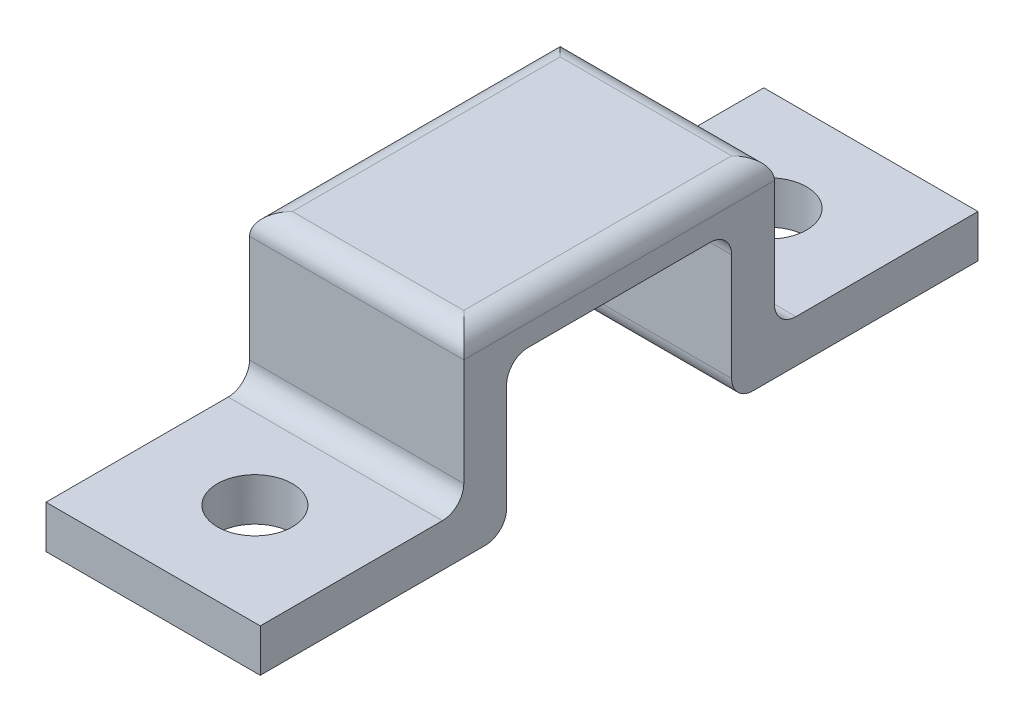
SolidWorks part; units mm, degrees
ref_plane "Front Plane" through (0, 0, 0) normal (0, 0, 1) x (1, 0, 0)
ref_plane "Top Plane" through (0, 0, 0) normal (0, 1, 0) x (1, 0, 0)
ref_plane "Right Plane" through (0, 0, 0) normal (1, 0, 0) x (0, 0, -1)
sketch "Sketch1" plane through (0, 0, 0) normal (1, 0, 0) x (0, 0, -1)
  line L0 (0, 0) -> (0, 14.0645) construction
  line L1 (-10.5, 0) -> (10.5, 0)
  line L2 (10.5, 0) -> (10.5, -14)
  line L3 (10.5, -14) -> (33.5, -14)
  line L4 (33.5, -14) -> (33.5, -10)
  line L5 (33.5, -10) -> (14.5, -10)
  line L6 (14.5, -10) -> (14.5, 4)
  line L7 (14.5, 4) -> (-14.5, 4)
  line L8 (-14.5, -10) -> (-14.5, 4)
  line L9 (-33.5, -10) -> (-14.5, -10)
  line L10 (-33.5, -14) -> (-33.5, -10)
  line L11 (-10.5, -14) -> (-33.5, -14)
  line L12 (-10.5, 0) -> (-10.5, -14)
  point P12 (0, 4)
  dimension "D1" = 10.5
  dimension "D2" = 14.5
  dimension "D3" = 4
  dimension "D4" = 23
  dimension "D5" = 14
  dimension "D6" = 4
extrude "Boss-Extrude1" add sketch "Sketch1" along normal blind 20
sketch "Sketch2" plane through (0, -10, 0) normal (0, 1, 0) x (1, 0, 0)
  line L0 (20, 33.5) -> (0, 33.5) construction
  line L1 (10, 33.5) -> (10, 14.5) construction
  line L2 (20, 14.5) -> (0, 14.5) construction
  circle A0 centre (10, 24) radius 3.5
  dimension "D1" = 7
extrude "Cut-Extrude1" cut sketch "Sketch2" against normal up to surface (4 mm away) up to face at (10, -14, -22)
mirror "Mirror1" about plane through (0, 0, 0) normal (0, 0, 1) of "Cut-Extrude1"
fillet "Fillet1" radius 2 10 edges at (10, -10, -14.5) (10, -10, 14.5) (10, 4, 14.5) (10, 4, -14.5) (10, 0, 10.5) (10, 0, -10.5) (10, -14, 10.5) (10, -14, -10.5) (20, 4, 0) (0, 4, 0)
